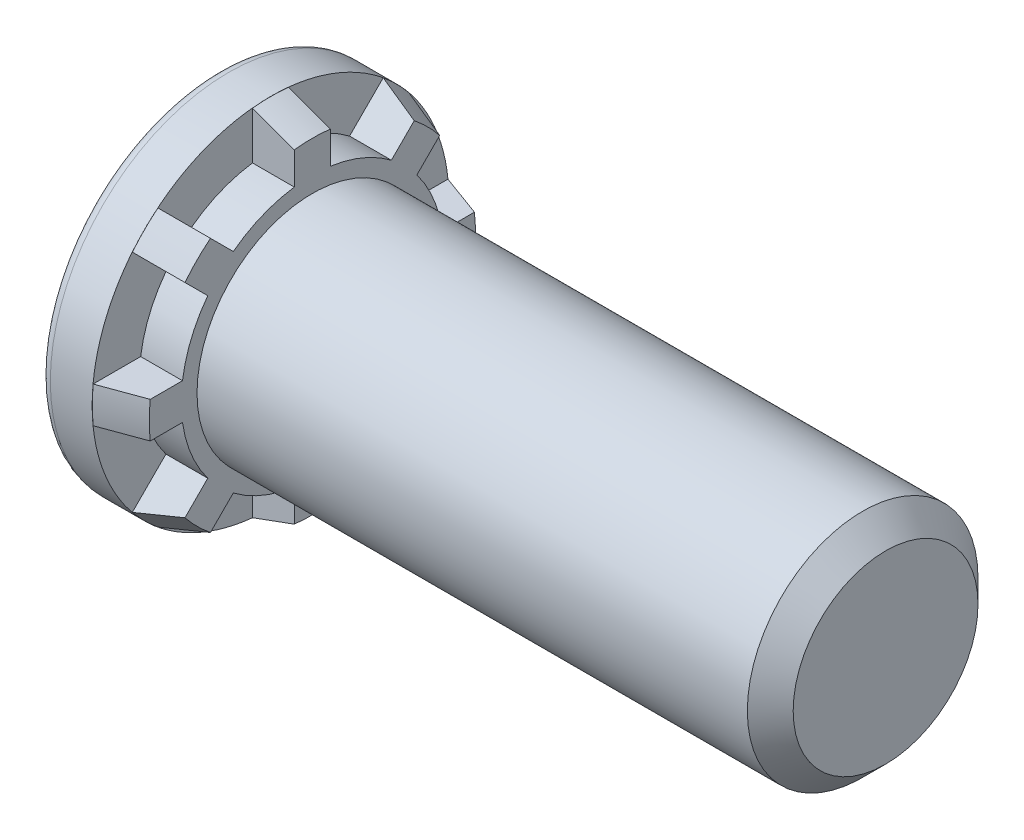
SolidWorks part; units mm, degrees
revolve "BaseBody" add sketch "BodySke" angle 360 about L6
sketch "BodySke" plane through (0, 0, 0) normal (0, 0, 1) x (1, 0, 0)
  line L0 (-2.159, 6.9342) -> (-2.159, 0)
  line L1 (1.7272, 6.7357) -> (1.7272, 4.7625)
  line L2 (0.0025, 7.3635) -> (1.7272, 6.7357)
  line L3 (1.7272, 4.7625) -> (24.4538, 4.7625)
  line L4 (25.4, 3.8163) -> (25.4, 0)
  line L5 (25.4, 0) -> (-2.159, 0)
  line L6 (0, 0) -> (50.554, 0) construction
  line L8 (25.4, 3.8163) -> (24.4538, 4.7625)
  line L9 (-1.7272, 7.366) -> (0, 7.366)
  line L10 (0.0025, 7.3635) -> (0, 7.3635)
  line L11 (1.5875, 19.05) -> (1.5875, -3.175) construction
  line L12 (0, 7.3635) -> (0, 7.366)
  arc A0 (-2.159, 6.9342) -> (-1.7272, 7.366) centre (-1.7272, 6.9342) cw
  dimension "Fillet_rad" = 0.4318
  dimension "Body_ch_ang" = 45
  dimension "Minor_dia" = 7.6327
  dimension "Diameter" = 9.525
  dimension "T_dim" = 2.159
  dimension "H_dia" = 14.732
  dimension "D2" = 0.0025
  dimension "D3" = 0.0025
  dimension "Length" = 25.4
  dimension "Advance" = 1.5875
  dimension "D1" = 20
  dimension "Clinch_ht" = 1.7272
cosmetic thread "ThreadCosmetic" [suppressed] parameters "Thread_length"=21.463, "Thread_minor"=7.6327
ref_plane "Plane1" through (0, 0, 0) normal (0, 0, 1) x (1, 0, 0)
ref_plane "Plane2" through (0, 0, 0) normal (0, 1, 0) x (1, 0, 0)
ref_plane "Plane3" through (0, 0, 0) normal (1, 0, 0) x (0, 0, -1)
sketch "ThdSchSke" plane through (0, 0, 0) normal (0, 0, 1) x (1, 0, 0)
  line L0 (3.937, -3.8163) -> (3.2745, -4.7625)
  line L1 (3.937, -3.8163) -> (4.5995, -4.7625)
  line L2 (4.5995, -4.7625) -> (4.5995, -5.9531)
  line L3 (-3.175, 0) -> (5.1513, 0) construction
  line L4 (0, -7.366) -> (0, 7.366) construction
  line L5 (4.5995, -5.9531) -> (3.2745, -5.9531)
  line L6 (3.2745, -5.9531) -> (3.2745, -4.7625)
  dimension "Diameter" = 9.525
  dimension "Thread_minor" = 7.6327
  dimension "Start" = 3.937
revolve "ThreadSchematic" [suppressed] cut sketch "ThdSchSke" angle 360 about L3
pattern_linear "ThdSchPat" [suppressed]
sketch "RibCutSke" plane through (1.7272, 1.7944, -0.091) normal (1, 0, 0) x (0, 0, -1)
  line L0 (0.6541, 3.5675) -> (0.6541, 5.5338)
  line L1 (3.1736, 2.5238) -> (4.5641, 3.9142)
  line L2 (0.6541, 2.9095) -> (0.6541, 2.4006) construction
  line L3 (-0.091, -1.7944) -> (-0.091, 5.0239) construction
  line L4 (-0.091, -1.7944) -> (0.6541, 2.9095) construction
  line L5 (-0.091, -1.7944) -> (2.7084, 2.0585) construction
  line L6 (2.7084, 2.0585) -> (2.3536, 1.7038) construction
  arc A1 (3.1736, 2.5238) -> (0.6541, 3.5675) centre (-0.091, -1.7944) ccw
  arc A2 (4.5641, 3.9142) -> (0.6541, 5.5338) centre (-0.091, -1.7944) ccw
  circle A3 centre (-0.091, -1.7944) radius 6.7357 construction
  circle A4 centre (-0.091, -1.7944) radius 4.7625 construction
  dimension "Rib_root_half_angle" = 9
  dimension "Rib_root_gap_angle" = 27
  dimension "Angle" = 45
extrude "RibCut" cut sketch "RibCutSke" against normal blind 1.7272
pattern_circular "RibCutsPat" count 8 every 45 about axis through (0, 0, 0) along (1, 0, 0) of "RibCut"
equation "' \"Length@BodySke\" = 1"
equation "' \"H_dia@BodySke\" = 0.58"
equation "' \"Start@ThdSchSke\" = 0.155"
equation "' \"T_dim@BodySke\" = 0.085"
equation "' \"Diameter@BodySke\" = 0.375"
equation "' \"Minor_dia@BodySke\" = 0.3005"
equation "' \"Advance@BodySke\" = 0.0625"
equation "\"Fillet_rad@BodySke\" =  \"T_dim@BodySke\" * 0.2"
equation "\"Clinch_ht@BodySke\" = \"T_dim@BodySke\" * 0.8"
equation "\"Num_ribs@RibCutsPat\" = 8"
equation "\"Angle@RibCutSke\" =\"Angle@RibCutsPat\""
equation "\"Rib_root_half_angle@RibCutSke\" = \"Angle@RibCutSke\" / 5"
equation "\"Rib_root_gap_angle@RibCutSke\" = \"Angle@RibCutSke\" - (2 * \"Rib_root_half_angle@RibCutSke\" )"
equation "\"Rib_root_dia@RibCutSke\" = \"Diameter@BodySke\""
equation "\"Inner_dia@RibCutSke\" = \"Diameter@BodySke\" + ( \"H_dia@BodySke\" - \"Diameter@BodySke\" ) / 4"
equation "\"Outer_dia@RibCutSke\" = \"H_dia@BodySke\""
equation "\"Depth@RibCut\" = \"Clinch_ht@BodySke\""
equation "\"Thread_length@ThreadCosmetic\" = \"Length@BodySke\" - \"Start@ThdSchSke\""
equation "\"Thread_minor@ThreadCosmetic\" = \"Minor_dia@BodySke\""
equation "\"Thread_minor@ThdSchSke\" = \"Minor_dia@BodySke\""
equation "\"Diameter@ThdSchSke\" = \"Diameter@BodySke\""
equation "\"Overcut@ThdSchSke\" = \"Diameter@BodySke\" * 1.25"
equation "\"Num_threads@ThdSchPat\" = int( \"Thread_length@ThreadCosmetic\" / \"Advance@BodySke\" + 0.999 )  + 1"
equation "\"Advance@ThdSchPat\" = \"Thread_length@ThreadCosmetic\" /  (\"Num_threads@ThdSchPat\" - 1) 'relax it"
equation "\"Num_threads@ThdSchPat\" = \"Num_threads@ThdSchPat\" - sgn( \"Num_threads@ThdSchPat\" - 1) '---chamfered tips only---"
